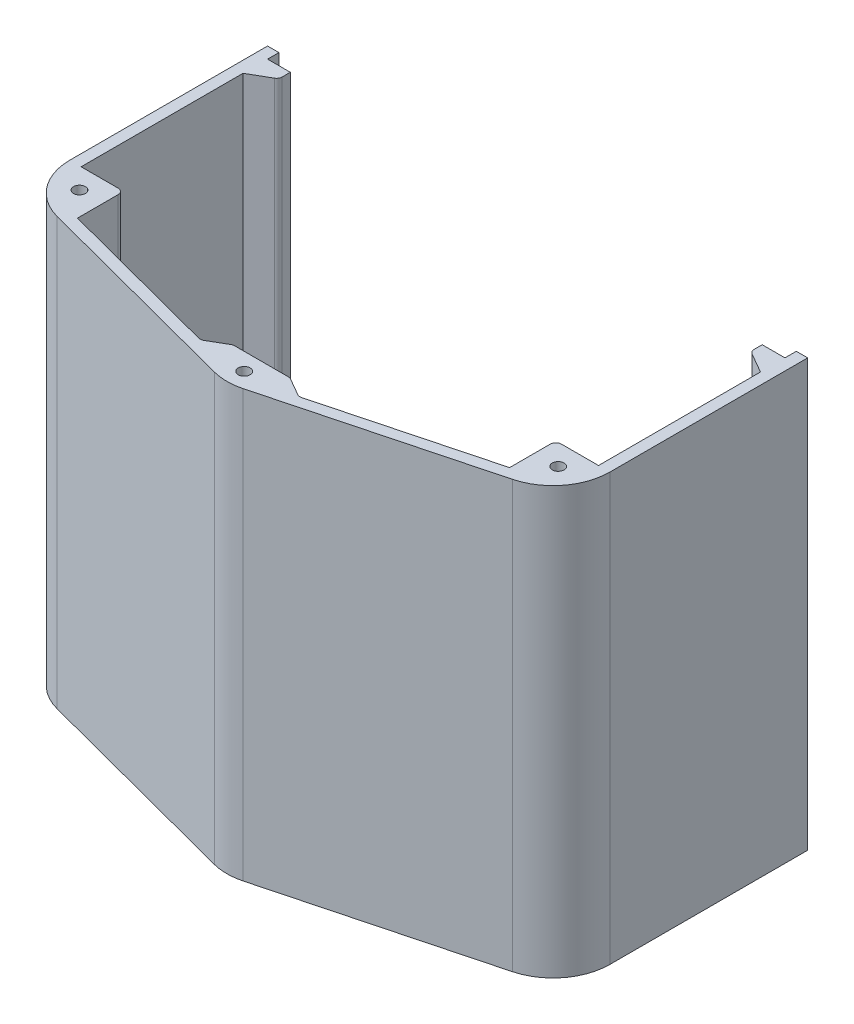
SolidWorks part; units mm, degrees
ref_plane "Front Plane" through (0, 0, 0) normal (0, 0, 1) x (1, 0, 0)
ref_plane "Top Plane" through (0, 0, 0) normal (0, 1, 0) x (1, 0, 0)
ref_plane "Right Plane" through (0, 0, 0) normal (1, 0, 0) x (0, 0, -1)
sketch "Sketch1" plane through (0, 0, 0) normal (0, 1, 0) x (1, 0, 0)
  line L0 (0, 0) -> (0, -110)
  line L2 (95, 0) -> (95, -69.5822)
  line L3 (80.0899, -88.9237) -> (5.0899, -108.6606)
  line L4 (-95, 0) -> (95, 0)
  line L5 (-95, 0) -> (-95, -69.5822)
  line L6 (-80.0899, -88.9237) -> (-5.0899, -108.6606)
  arc A0 (5.0899, -108.6606) -> (-5.0899, -108.6606) centre (0, -89.3191) cw
  arc A1 (95, -69.5822) -> (80.0899, -88.9237) centre (75, -69.5822) cw
  arc A2 (-95, -69.5822) -> (-80.0899, -88.9237) centre (-75, -69.5822) ccw
  point P12 (95, -85)
  point P15 (-95, -85)
  dimension "D7" = 20
  dimension "D1" = 110
  dimension "D2" = 95
  dimension "D3" = 85
  dimension "D4" = 85
  dimension "D5" = 95
  dimension "D6" = 190
extrude "Boss-Extrude1" add sketch "Sketch1" along normal blind 150 contours L6 A0 L3 A1 L2 L4 L5 A2
shell "Shell2" thickness 4
sketch "Sketch3" plane through (0, 0, 0) normal (0, 1, 0) x (1, 0, 0)
  line L0 (-91, 0) -> (-91, -4) construction
  line L1 (-91, 0) -> (-91, -69.5822) construction
  line L2 (-91, -4) -> (-83, -4)
  line L3 (-83, -4) -> (-83, -8)
  line L4 (-83, -8) -> (-91, -12.6188)
  line L5 (-91, -69.5822) -> (-76, -69.5822)
  line L9 (-95, -69.5822) -> (-91, -69.5822)
  line L10 (-91, -12.6188) -> (-91, -4)
  line L11 (-76, -69.5822) -> (-76, -85.8638)
  line L12 (-79.0719, -85.0554) -> (-4.0719, -104.7923) construction
  line L13 (-76, -85.8638) -> (-80.3003, -88.8671)
  line L14 (-95, -69.5822) -> (-90.8398, -81.7929)
  line L15 (-90.8398, -81.7929) -> (-80.3003, -88.8671)
  line L16 (0, -60.1255) -> (0, 60.1255) construction
  line L17 (91, -69.5822) -> (76, -69.5822)
  line L18 (76, -69.5822) -> (76, -85.8638)
  line L19 (76, -85.8638) -> (80.3003, -88.8671)
  line L20 (90.8398, -81.7929) -> (80.3003, -88.8671)
  line L21 (95, -69.5822) -> (90.8398, -81.7929)
  line L22 (95, -69.5822) -> (91, -69.5822)
  line L23 (83, -8) -> (91, -12.6188)
  line L24 (83, -4) -> (83, -8)
  line L25 (91, -4) -> (83, -4)
  line L26 (91, -12.6188) -> (91, -4)
  arc A1 (-95, -69.5822) -> (-80.0899, -88.9237) centre (-75, -69.5822) ccw construction
  dimension "D1" = 4
  dimension "D2" = 8
  dimension "D3" = 4
  dimension "D4" = 15
  dimension "D5" = 90
  dimension "D6" = 120
extrude "Boss-Extrude2" add sketch "Sketch3" along normal blind 150
fillet "Fillet1" radius 2 4 edges at (83, 75, 8) (-83, 75, 8) (-76, 75, 69.5822) (76, 75, 69.5822)
sketch "Sketch4" plane through (0, 0, 0) normal (0, 1, 0) x (1, 0, 0)
  line L0 (-91, -69.5822) -> (-76, -85.8638) construction
  line L1 (-84.1973, -76.9662) -> (-76.5858, -70.168) construction
  line L2 (76, -85.8638) -> (91, -69.5822) construction
  line L3 (84.1973, -76.9662) -> (76.5858, -70.168) construction
  arc A0 (-76, -71.5822) -> (-78, -69.5822) centre (-78, -71.5822) ccw construction
  arc A2 (78, -69.5822) -> (76, -71.5822) centre (78, -71.5822) ccw construction
  circle A4 centre (84.1973, -76.9662) radius 2.1
  circle A5 centre (-84.1973, -76.9662) radius 2.1
  dimension "D1" = 4.2
  dimension "D3" = 4.2
  dimension "D2" = 10.2054
extrude "Cut-Extrude1" cut sketch "Sketch4" along normal blind 150
sketch "Sketch5" plane through (0, 0, 0) normal (0, 1, 0) x (1, 0, 0)
  line L0 (-83, -4) -> (83, -4)
  line L1 (83, -4) -> (83, -6.8453)
  line L2 (83, -6.8453) -> (-83, -6.8453)
  line L3 (-83, -6.8453) -> (-83, -4)
extrude "Boss-Extrude3" add sketch "Sketch5" along normal blind 10
sketch "Sketch6" plane through (0, 0, 0) normal (0, 1, 0) x (1, 0, 0)
  line L0 (0, -101.1191) -> (0, -105.3191) construction
  line L1 (0, -101.1191) -> (0, -97.1191) construction
  line L2 (0, -60.1255) -> (0, 60.1255) construction
  line L4 (10, -97.1191) -> (17.2732, -101.3182)
  line L7 (10, -97.1191) -> (-10, -97.1191)
  line L8 (-10, -97.1191) -> (-17.2732, -101.3182)
  line L9 (-76, -85.8638) -> (-4.0719, -104.7923) construction
  line L16 (-17.2732, -101.3182) -> (0, -107.9721)
  line L17 (0, -107.9721) -> (17.2732, -101.3182)
  arc A0 (-4.0719, -104.7923) -> (4.0719, -104.7923) centre (0, -89.3191) ccw construction
  dimension "D1" = 4.2
  dimension "D2" = 4
  dimension "D3" = 10
  dimension "D5" = 150
extrude "Boss-Extrude6" add sketch "Sketch6" along normal blind 150
fillet "Fillet2" radius 2 4 edges at (17.2732, 75, 101.3182) (10, 75, 97.1191) (-17.2732, 75, 101.3182) (-10, 75, 97.1191)
sketch "Sketch7" plane through (0, 0, 0) normal (0, 1, 0) x (1, 0, 0)
  line L0 (0, -97.1191) -> (0, -103.2191) construction
  line L1 (9.4641, -97.1191) -> (-9.4641, -97.1191) construction
  circle A0 centre (0, -103.2191) radius 2.1
  dimension "D2" = 4.2
  dimension "D1" = 6.1
extrude "Cut-Extrude3" cut sketch "Sketch7" along normal blind 150
